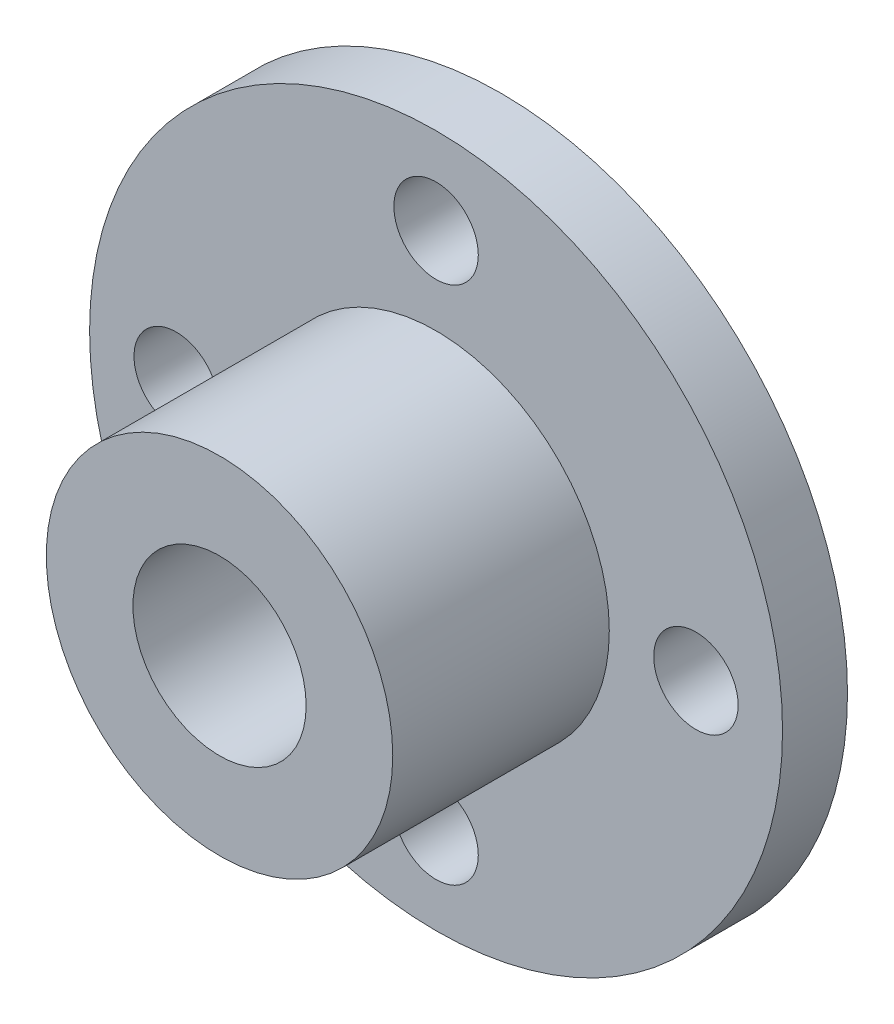
SolidWorks part; units mm, degrees
ref_plane "Alzado" through (0, 0, 0) normal (0, 0, 1) x (1, 0, 0)
ref_plane "Planta" through (0, 0, 0) normal (0, 1, 0) x (1, 0, 0)
ref_plane "Vista lateral" through (0, 0, 0) normal (1, 0, 0) x (0, 0, -1)
sketch "Croquis1" plane through (0, 0, 0) normal (0, 0, 1) x (1, 0, 0)
  circle A0 centre (0, 0) radius 16
  dimension "D1" = 32
extrude "Saliente-Extruir1" add sketch "Croquis1" along normal blind 3
sketch "Croquis2" plane through (0, 0, 3) normal (0, 0, 1) x (1, 0, 0)
  circle A0 centre (0, 0) radius 8
  circle A1 centre (0, 0) radius 4
  dimension "D1" = 8
  dimension "D2" = 16
extrude "Saliente-Extruir2" add sketch "Croquis2" along normal blind 10
sketch "Croquis3" plane through (0, 0, 3) normal (0, 0, 1) x (1, 0, 0)
  line L0 (0, 0) -> (0, 12) construction
  circle A0 centre (0, 0) radius 8
  circle A2 centre (0, 0) radius 12
  circle A3 centre (0, 12) radius 1.95
  circle A4 centre (12, 0) radius 1.95
  circle A5 centre (0, -12) radius 1.95
  circle A6 centre (-12, 0) radius 1.95
  dimension "D1" = 16
  dimension "D2" = 24
  dimension "D3" = 3.9
  dimension "D6" = 12
  dimension "D5" = 12
  dimension "D4" = 4
extrude "Cortar-Extruir1" cut sketch "Croquis3" against normal blind 3 contours A2 A6 | A2 A3 | A3 L0 A2 | A2 A5 | A2 A5 | A2 A4 | A2 A4
